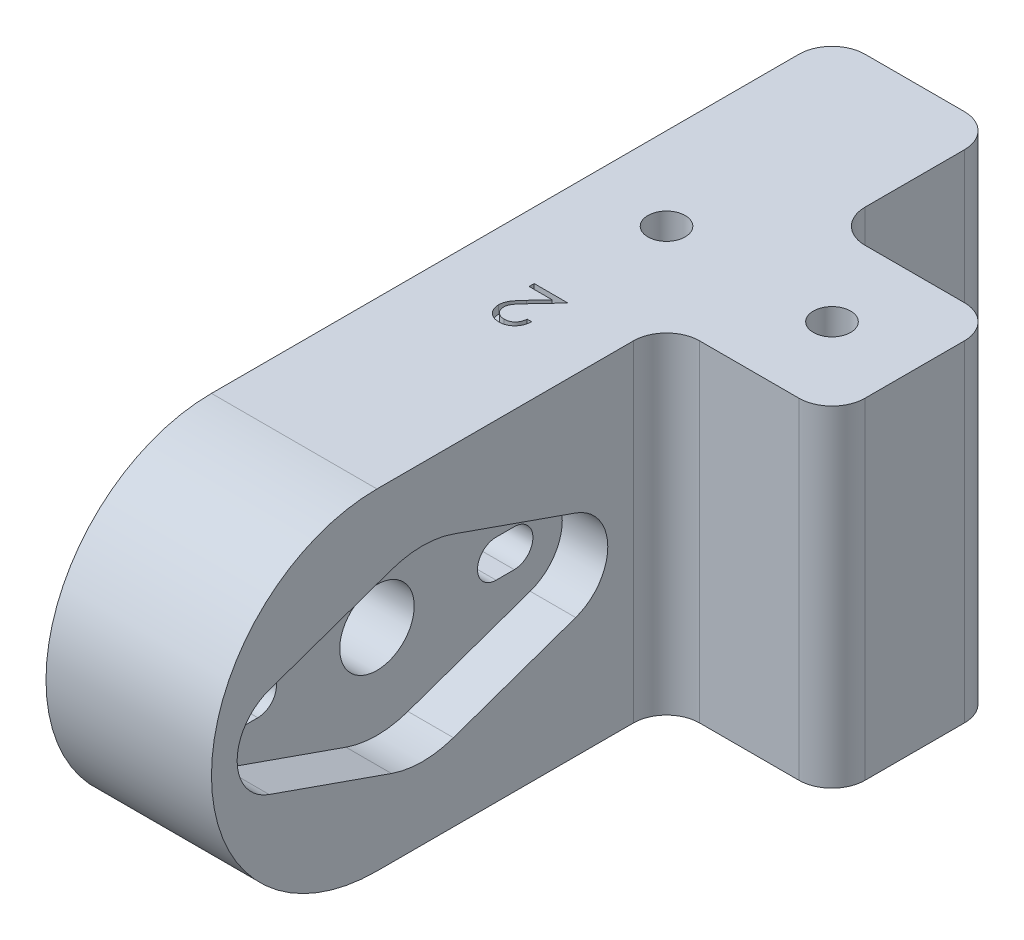
SolidWorks part; units mm, degrees
ref_plane "Alzado" through (0, 0, 0) normal (0, 0, 1) x (1, 0, 0)
ref_plane "Planta" through (0, 0, 0) normal (0, 1, 0) x (1, 0, 0)
ref_plane "Vista lateral" through (0, 0, 0) normal (1, 0, 0) x (0, 0, -1)
sketch "Croquis1" plane through (0, 0, 0) normal (0, 1, 0) x (1, 0, 0)
  line L0 (0, 0) -> (40, 0)
  line L1 (40, 0) -> (40, 20)
  line L2 (40, 20) -> (20, 20)
  line L3 (20, 20) -> (20, 40)
  line L4 (20, 40) -> (0, 40)
  line L5 (0, 40) -> (0, 0)
extrude "Saliente-Extruir1" add sketch "Croquis1" along normal blind 40
sketch "Croquis2" plane through (0, 40, 0) normal (0, 1, 0) x (1, 0, 0)
  line L0 (40, 0) -> (40, 10) construction
  line L1 (40, 0) -> (40, 20) construction
  line L2 (40, 10) -> (30, 10) construction
  line L3 (0, 0) -> (10, 0) construction
  line L4 (0, 0) -> (40, 0) construction
  line L5 (10, 0) -> (10, 10) construction
  circle A0 centre (30, 10) radius 2.25
  circle A1 centre (10, 10) radius 2.25
extrude "Cortar-Extruir1" cut sketch "Croquis2" against normal up to next
sketch "Croquis3" plane through (0, 0, 0) normal (-1, 0, 0) x (0, 0, 1)
  line L2 (0, 40) -> (35, 40)
  line L3 (0, 0) -> (35, 0)
  arc A0 (35, 0) -> (35, 40) centre (35, 20) ccw
extrude "Saliente-Extruir2" add sketch "Croquis3" against normal blind 20
sketch "Croquis5" plane through (0, 0, -40) normal (0, 0, -1) x (-1, 0, 0)
  line L0 (-20, 0) -> (-10, 0) construction
  line L1 (-20, 0) -> (0, 0) construction
  line L2 (-10, 0) -> (-10, 30) construction
  circle A0 centre (-10, 30) radius 4.15
extrude "Cortar-Extruir2" cut sketch "Croquis5" against normal blind 25
fillet "Redondeo2" radius 4 6 edges at (0, 20, -40) (20, 20, 0) (40, 20, 0) (40, 20, -20) (20, 20, -20) (20, 20, -40)
sketch "Croquis9" plane through (20, 0, 0) normal (1, 0, 0) x (0, 0, -1)
  line L0 (-4, 0) -> (-4, 20) construction
  line L1 (-4, 0) -> (-4, 40) construction
sketch "Croquis10" plane through (20, 0, 0) normal (1, 0, 0) x (0, 0, -1)
  line L0 (-4, 20) -> (-55, 20) construction
  line L1 (-55, 20) -> (-29.5, 20) construction
  line L2 (-29.5, 20) -> (-14, 20) construction
  line L3 (-29.5, 20) -> (-45, 20) construction
  arc A0 (-35, 40) -> (-35, 0) centre (-35, 20) ccw construction
  circle A1 centre (-29.5, 20) radius 4.5
  circle A2 centre (-14, 20) radius 2.25
  circle A3 centre (-45, 20) radius 2.25
extrude "Cortar-Extruir3" cut sketch "Croquis10" against normal up to next
sketch "Croquis12" plane through (20, 0, 0) normal (1, 0, 0) x (0, 0, -1)
  line L0 (-29.5, 20) -> (-7, 20) construction
  line L1 (-29.5, 20) -> (-52, 20) construction
  line L2 (-29.5, 20) -> (-29.9649, 30.9902) construction
  line L3 (-29.5, 20) -> (-29.0351, 9.0098) construction
  line L4 (-45, 20) -> (-46.1, 20) construction
  line L5 (-14, 20) -> (-12.9, 20) construction
  line L6 (-15.1, 20) -> (-12.9, 20) construction
  line L7 (-43.9, 20) -> (-46.1, 20) construction
  line L8 (-15.1, 22.25) -> (-12.9, 22.25)
  line L9 (-15.1, 17.75) -> (-12.9, 17.75)
  line L11 (-43.9, 17.75) -> (-46.1, 17.75)
  line L12 (-43.9, 22.25) -> (-46.1, 22.25)
  arc A1 (-43.9, 17.75) -> (-43.9, 22.25) centre (-43.9, 20) ccw
  arc A2 (-46.1, 22.25) -> (-46.1, 17.75) centre (-46.1, 20) ccw
  arc A3 (-15.1, 22.25) -> (-15.1, 17.75) centre (-15.1, 20) ccw
  arc A4 (-12.9, 17.75) -> (-12.9, 22.25) centre (-12.9, 20) ccw
  point P17 (-45, 20)
  point P18 (-14, 20)
extrude "Cortar-Extruir5" cut sketch "Croquis12" against normal up to next
sketch "Croquis14" plane through (20, 0, 0) normal (1, 0, 0) x (0, 0, -1)
  line L0 (-48.0217, 25.4724) -> (-33.244, 30.6617)
  line L1 (-48.0217, 14.5276) -> (-33.244, 9.3383)
  line L2 (-10.9783, 25.4724) -> (-25.756, 30.6617)
  line L3 (-10.9783, 14.5276) -> (-25.756, 9.3383)
  arc A0 (-48.0217, 25.4724) -> (-48.0217, 14.5276) centre (-46.1, 20) ccw
  arc A1 (-10.9783, 14.5276) -> (-10.9783, 25.4724) centre (-12.9, 20) ccw
  arc A2 (-33.244, 9.3383) -> (-25.756, 9.3383) centre (-29.5, 20) ccw
  arc A4 (-25.756, 30.6617) -> (-33.244, 30.6617) centre (-29.5, 20) ccw
  dimension "D1" = 11.3
extrude "Cortar-Extruir6" cut sketch "Croquis14" against normal blind 5.5
sketch "Croquis15" plane through (0, 40, 0) normal (0, 1, 0) x (1, 0, 0)
  line L0 (20, -4) -> (0, -4) construction
  line L1 (0, 36) -> (0, -35) construction
  text T0 "2" font "Century Gothic" height 6
extrude "Cortar-Extruir7" cut sketch "Croquis15" against normal blind 1
